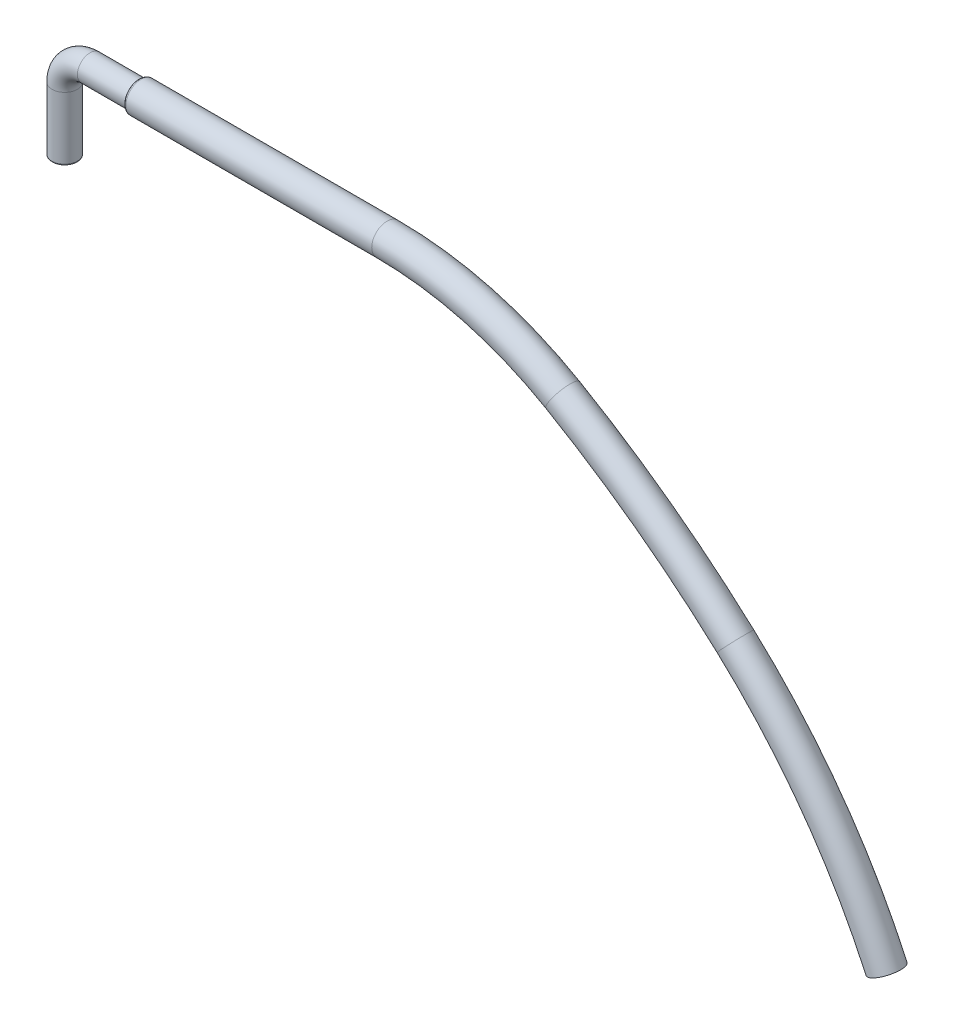
SolidWorks part; units mm, degrees
ref_plane "Alzado" through (0, 0, 0) normal (0, 0, 1) x (1, 0, 0)
ref_plane "Planta" through (0, 0, 0) normal (0, 1, 0) x (1, 0, 0)
ref_plane "Vista lateral" through (0, 0, 0) normal (1, 0, 0) x (0, 0, -1)
sketch "Croquis1" plane through (0, 0, 0) normal (0, 0, 1) x (1, 0, 0)
  line L0 (0, -10) -> (0, -35)
  line L1 (10, 0) -> (50, 0)
  line L2 (0, -10) -> (23.5725, -10) construction
  line L3 (50, 0) -> (50, 2.9617) construction
  line L4 (50, 0) -> (53.7086, 0) construction
  line L5 (16, 0) -> (16, 26.592) construction
  line L6 (0, -31) -> (18.2487, -31) construction
  line L7 (46, 0) -> (46, 28.3563) construction
  line L8 (0, -11) -> (26.2947, -11) construction
  arc A0 (0, -10) -> (10, 0) centre (10, -10) cw
  point P6 (0, 0)
  dimension "D1" = 10
  dimension "D2" = 25
  dimension "D3" = 40
  dimension "D4" = 4
  dimension "D5" = 30
  dimension "D6" = 4
  dimension "D7" = 20
ref_plane "Plano1" through (0, -35, 0) normal (0, -1, 0) x (1, 0, 0)
sketch "Croquis2" plane through (0, -35, 0) normal (0, -1, 0) x (1, 0, 0)
  line L0 (0, 0) -> (0, -10.1083) construction
  line L1 (0, 0) -> (-12.2077, 0) construction
  circle A0 centre (0, 0) radius 5
  dimension "D1" = 10
sweep "Barrer1" add profiles "Croquis2" path "Croquis1"
shell "Vaciado2" thickness 2
fillet "Redondeo1" radius 0.5 4 edges at (3, -35, 0) (5, -35, 0) (50, -5, 0) (50, -3, 0)
sketch "Croquis3" plane through (0, -35, 0) normal (0, -1, 0) x (1, 0, 0)
  line L0 (0, 0) -> (10.9751, 0) construction
  line L1 (0, 0) -> (0, -13.0055) construction
sketch "Croquis5" plane through (50, 0, 0) normal (1, 0, 0) x (0, 0, -1)
  line L0 (0, 0) -> (12.3974, 0) construction
sketch "Croquis6" plane through (0, 0, 0) normal (0, 0, 1) x (1, 0, 0)
  line L0 (29.0946, 0) -> (126.9484, 0)
  arc A0 (126.9484, 0) -> (196.1398, -18.5978) centre (126.9484, -138.0089) cw
  arc A1 (196.1398, -18.5978) -> (264.2523, -68.6673) centre (0.8635, -355.6074) cw
  arc A2 (264.2523, -68.6673) -> (323.7944, -150.7632) centre (92.231, -256.0701) cw
ref_plane "Plano2" through (29.0946, 0, 0) normal (1, 0, 0) x (0, 0, -1)
sketch "Croquis7" plane through (29.0946, 0, 0) normal (1, 0, 0) x (0, 0, -1)
  circle A0 centre (0, 0) radius 6
  dimension "D1" = 12
sweep "Barrer2" add profiles "Croquis7" path "Croquis6"
shell "Vaciado3" thickness 4
fillet "Redondeo2" radius 1 1 edges at (29.0946, 0, -6)
